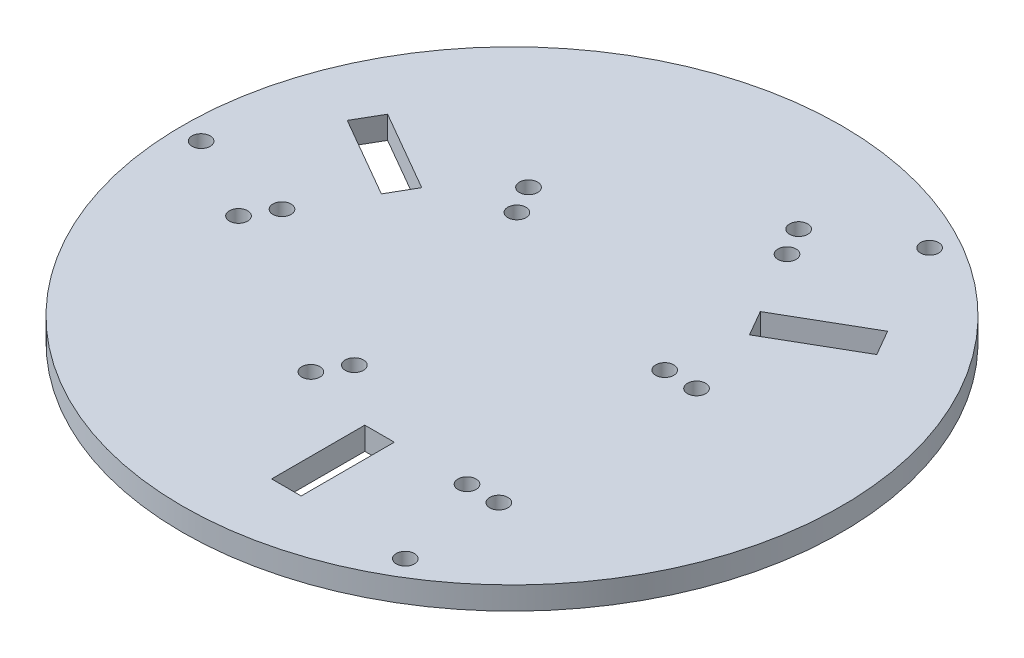
SolidWorks part; units mm, degrees
ref_plane "Front" through (0, 0, 0) normal (0, 0, 1) x (1, 0, 0)
ref_plane "Top" through (0, 0, 0) normal (0, 1, 0) x (1, 0, 0)
ref_plane "Right" through (0, 0, 0) normal (1, 0, 0) x (0, 0, -1)
sketch "Sketch1" plane through (0, 0, 0) normal (0, 1, 0) x (1, 0, 0)
  circle A0 centre (0, 0) radius 72.5
  dimension "D1" = 145
extrude "Boss-Extrude1" add sketch "Sketch1" along normal blind 5
sketch "Sketch7" plane through (0, 5, 0) normal (0, 1, 0) x (1, 0, 0)
  line L0 (-22.6721, 26.3122) -> (-19.1721, 20.25) construction
  line L1 (-19.1721, 20.25) -> (18.5, 42) construction
  line L2 (18.5, 42) -> (15, 48.0622) construction
  line L3 (15, 48.0622) -> (-22.6721, 26.3122) construction
  line L4 (0, -2.75) -> (0, 2.75) construction
  line L5 (-2.75, 0) -> (2.75, 0) construction
  line L7 (35.3633, 33.2608) -> (38.6133, 27.6316) construction
  line L8 (26.4865, 28.1358) -> (44.24, 38.3858)
  line L9 (26.4865, 28.1358) -> (29.7365, 22.5066)
  line L10 (29.7365, 22.5066) -> (47.49, 32.7566)
  line L11 (44.24, 38.3858) -> (47.49, 32.7566)
  circle A0 centre (15, 48.0622) radius 2
  circle A1 centre (18.5, 42) radius 2
  circle A2 centre (-22.6721, 26.3122) radius 2
  circle A3 centre (-19.1721, 20.25) radius 2
  circle A4 centre (32.9652, 58.9029) radius 2
  circle A5 centre (0, 0) radius 72.5 construction
  dimension "D6" = 4
  dimension "D10" = 4
  dimension "D1" = 7
  dimension "D2" = 43.5
  dimension "D3" = 15
  dimension "D4" = 16
  dimension "D5" = 42
  dimension "D7" = 6.5
  dimension "D8" = 20.5
  dimension "D9" = 60
  dimension "D11" = 67.5
extrude "Cut-Extrude6" cut sketch "Sketch7" against normal up to next
pattern_circular "CirPattern1" count 3 over 360 about axis through (0, 0, 0) along (0, 1, 0) of "Cut-Extrude6"
